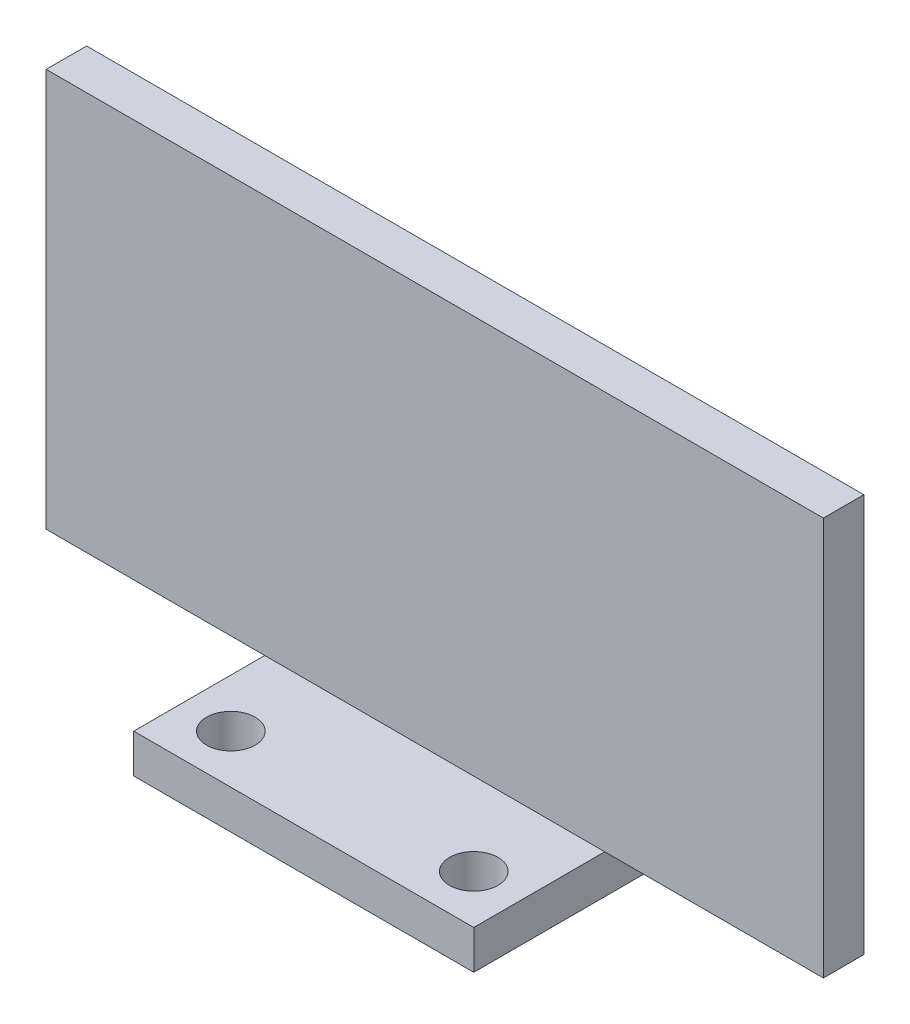
SolidWorks part; units mm, degrees
ref_plane "Front Plane" through (0, 0, 0) normal (0, 0, 1) x (1, 0, 0)
ref_plane "Top Plane" through (0, 0, 0) normal (0, 1, 0) x (1, 0, 0)
ref_plane "Right Plane" through (0, 0, 0) normal (1, 0, 0) x (0, 0, -1)
sketch "Sketch1" plane through (0, 0, 0) normal (0, 1, 0) x (1, 0, 0)
  line L1 (0, 0) -> (35, 0)
  line L2 (0, 0) -> (0, 30)
  line L3 (0, 30) -> (35, 30)
  line L4 (35, 0) -> (35, 30)
  circle A0 centre (5, 25) radius 2.5
  circle A4 centre (30, 25) radius 2.5
  circle A5 centre (5, 5) radius 2.5
  circle A6 centre (30, 5) radius 2.5
  point P13 (0, 0)
  point P15 (0, 0)
  dimension "D3" = 5
  dimension "D1" = 30
  dimension "D2" = 35
  dimension "D4" = 5
  dimension "5" = 5
  dimension "D5" = 5
  dimension "D6" = 5
  dimension "D7" = 5
  dimension "D8" = 5
  dimension "D9" = 5
  dimension "D10" = 5
extrude "Boss-Extrude1" add sketch "Sketch1" along normal blind 4
sketch "Sketch2" plane through (0, 4, 0) normal (0, 1, 0) x (1, 0, 0)
  line L1 (-22.5, 17.6514) -> (57.5, 17.6514)
  line L2 (-22.5, 17.6514) -> (-22.5, 13.4881)
  line L3 (-22.5, 13.4881) -> (57.5, 13.4881)
  line L4 (57.5, 17.6514) -> (57.5, 13.4881)
  line L6 (17.5, 0) -> (17.5, 40.1823) construction
  line L7 (0, -2.2) -> (0, 2.2) construction
  dimension "D1" = 80
  dimension "D2" = 17.5
  dimension "D3" = 40
extrude "Boss-Extrude2" add sketch "Sketch2" along normal blind 41
